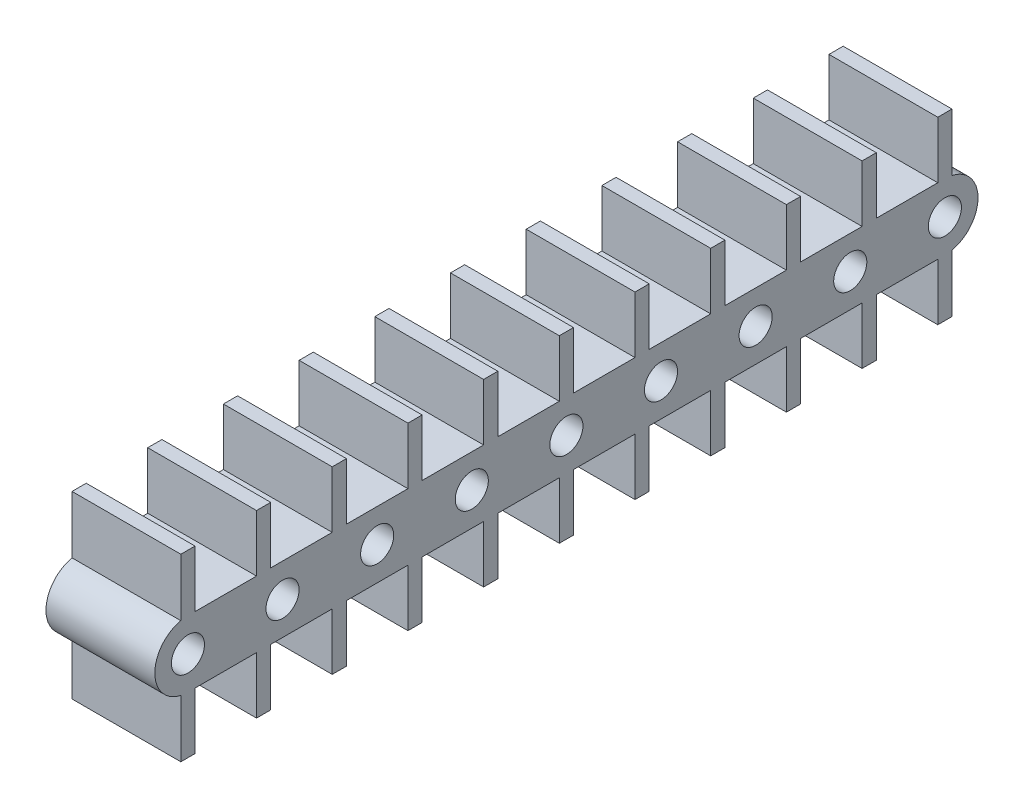
SolidWorks part; units mm, degrees
ref_plane "Front" through (0, 0, 0) normal (0, 0, 1) x (1, 0, 0)
ref_plane "Top" through (0, 0, 0) normal (0, 1, 0) x (1, 0, 0)
ref_plane "Right" through (0, 0, 0) normal (1, 0, 0) x (0, 0, -1)
sketch "Sketch1" plane through (0, 0, 0) normal (1, 0, 0) x (0, 0, -1)
  line L0 (0, 0) -> (800, 0) construction
  line L1 (7.5, 35) -> (72.5, 35)
  line L2 (7.5, -35) -> (72.5, -35)
  line L3 (400, 35) -> (400, -35) construction
  line L4 (407.5, 35) -> (472.5, 35)
  line L6 (392.5, 35) -> (392.5, 95)
  line L7 (392.5, 95) -> (407.5, 95)
  line L8 (407.5, 35) -> (407.5, 95)
  line L9 (487.5, 35) -> (487.5, 95)
  line L10 (472.5, 95) -> (487.5, 95)
  line L11 (472.5, 35) -> (472.5, 95)
  line L12 (567.5, 35) -> (567.5, 95)
  line L13 (552.5, 95) -> (567.5, 95)
  line L14 (552.5, 35) -> (552.5, 95)
  line L15 (647.5, 35) -> (647.5, 95)
  line L16 (632.5, 95) -> (647.5, 95)
  line L17 (632.5, 35) -> (632.5, 95)
  line L18 (727.5, 35) -> (727.5, 95)
  line L19 (712.5, 95) -> (727.5, 95)
  line L20 (712.5, 35) -> (712.5, 95)
  line L21 (807.5, 34.187) -> (807.5, 95)
  line L22 (792.5, 95) -> (807.5, 95)
  line L23 (792.5, 35) -> (792.5, 95)
  line L24 (327.5, 35) -> (327.5, 95)
  line L25 (312.5, 95) -> (327.5, 95)
  line L26 (312.5, 35) -> (312.5, 95)
  line L27 (247.5, 35) -> (247.5, 95)
  line L28 (232.5, 95) -> (247.5, 95)
  line L29 (232.5, 35) -> (232.5, 95)
  line L30 (167.5, 35) -> (167.5, 95)
  line L31 (152.5, 95) -> (167.5, 95)
  line L32 (152.5, 35) -> (152.5, 95)
  line L33 (87.5, 35) -> (87.5, 95)
  line L34 (72.5, 95) -> (87.5, 95)
  line L35 (72.5, 35) -> (72.5, 95)
  line L36 (7.5, 35) -> (7.5, 95)
  line L37 (-7.5, 95) -> (7.5, 95)
  line L38 (-7.5, 34.187) -> (-7.5, 95)
  line L39 (792.5, -35) -> (792.5, -95)
  line L40 (792.5, -95) -> (807.5, -95)
  line L41 (807.5, -34.187) -> (807.5, -95)
  line L42 (712.5, -35) -> (712.5, -95)
  line L43 (712.5, -95) -> (727.5, -95)
  line L44 (727.5, -35) -> (727.5, -95)
  line L45 (632.5, -35) -> (632.5, -95)
  line L46 (632.5, -95) -> (647.5, -95)
  line L47 (647.5, -35) -> (647.5, -95)
  line L48 (552.5, -35) -> (552.5, -95)
  line L49 (552.5, -95) -> (567.5, -95)
  line L50 (567.5, -35) -> (567.5, -95)
  line L51 (472.5, -35) -> (472.5, -95)
  line L52 (472.5, -95) -> (487.5, -95)
  line L53 (487.5, -35) -> (487.5, -95)
  line L54 (407.5, -35) -> (407.5, -95)
  line L55 (392.5, -95) -> (407.5, -95)
  line L56 (392.5, -35) -> (392.5, -95)
  line L57 (312.5, -35) -> (312.5, -95)
  line L58 (327.5, -35) -> (327.5, -95)
  line L59 (312.5, -95) -> (327.5, -95)
  line L60 (247.5, -35) -> (247.5, -95)
  line L61 (232.5, -95) -> (247.5, -95)
  line L62 (232.5, -35) -> (232.5, -95)
  line L63 (167.5, -35) -> (167.5, -95)
  line L64 (152.5, -95) -> (167.5, -95)
  line L65 (152.5, -35) -> (152.5, -95)
  line L66 (87.5, -35) -> (87.5, -95)
  line L67 (72.5, -95) -> (87.5, -95)
  line L68 (72.5, -35) -> (72.5, -95)
  line L69 (7.5, -35) -> (7.5, -95)
  line L70 (-7.5, -95) -> (7.5, -95)
  line L71 (-7.5, -34.187) -> (-7.5, -95)
  line L72 (87.5, -35) -> (152.5, -35)
  line L73 (167.5, -35) -> (232.5, -35)
  line L74 (247.5, -35) -> (312.5, -35)
  line L75 (87.5, 35) -> (152.5, 35)
  line L76 (167.5, 35) -> (232.5, 35)
  line L77 (407.5, -35) -> (472.5, -35)
  line L78 (327.5, -35) -> (392.5, -35)
  line L79 (487.5, -35) -> (552.5, -35)
  line L80 (487.5, 35) -> (552.5, 35)
  line L81 (567.5, 35) -> (632.5, 35)
  line L82 (567.5, -35) -> (632.5, -35)
  line L83 (647.5, 35) -> (712.5, 35)
  line L84 (647.5, -35) -> (712.5, -35)
  line L85 (727.5, -35) -> (792.5, -35)
  line L86 (727.5, 35) -> (792.5, 35)
  line L87 (327.5, 35) -> (392.5, 35)
  line L88 (247.5, 35) -> (312.5, 35)
  arc A0 (-7.5, 34.187) -> (-7.5, -34.187) centre (0, 0) ccw
  arc A1 (807.5, -34.187) -> (807.5, 34.187) centre (800, 0) ccw
  circle A2 centre (0, 0) radius 17.5
  circle A3 centre (800, 0) radius 17.5
  circle A4 centre (100, 0) radius 17.5
  circle A5 centre (200, 0) radius 17.5
  circle A6 centre (300, 0) radius 17.5
  circle A7 centre (400, 0) radius 17.5
  circle A8 centre (500, 0) radius 17.5
  circle A9 centre (600, 0) radius 17.5
  circle A10 centre (700, 0) radius 17.5
  point P3 (400, 0)
  point P32 (400, 95)
  point P117 (0, 0)
  point P118 (0, 0)
  point P119 (0, 0)
  dimension "D1" = 800
  dimension "D2" = 35
  dimension "D5" = 60
  dimension "D6" = 15
  dimension "D7" = 6
  dimension "D4" = 8
  dimension "D8" = 6
extrude "Boss-Extrude1" add sketch "Sketch1" along normal blind 115
